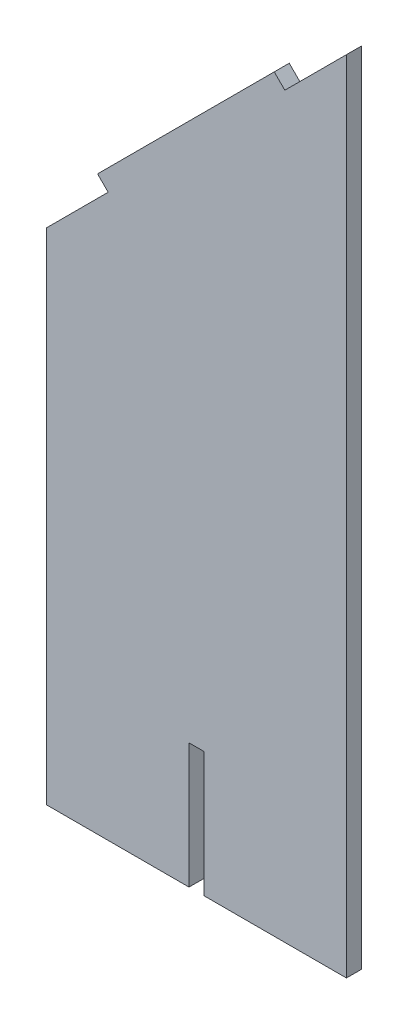
SolidWorks part; units mm, degrees
ref_plane "Plan de face" through (0, 0, 0) normal (0, 0, 1) x (1, 0, 0)
ref_plane "Plan de dessus" through (0, 0, 0) normal (0, 1, 0) x (1, 0, 0)
ref_plane "Plan de droite" through (0, 0, 0) normal (1, 0, 0) x (0, 0, -1)
sketch "Esquisse1" plane through (0, 0, 0) normal (0, 0, 1) x (1, 0, 0)
  line L1 (0, 0) -> (28.5, 0)
  line L2 (0, 0) -> (0, 100)
  line L3 (0, 100) -> (60, 100)
  line L4 (60, 0) -> (60, 100)
  line L5 (60, 100) -> (0, 100)
  line L9 (60, 160) -> (60, 100)
  line L10 (28.5, 0) -> (28.5, 25)
  line L11 (28.5, 25) -> (31.5, 25)
  line L12 (31.5, 25) -> (31.5, 0)
  line L13 (0, 100) -> (12.3213, 112.3213)
  line L14 (12.3213, 112.3213) -> (10.2, 114.4427)
  line L15 (10.2, 114.4427) -> (45.5554, 149.798)
  line L16 (31.5, 0) -> (60, 0)
  line L17 (45.5554, 149.798) -> (47.6767, 147.6767)
  line L18 (47.6767, 147.6767) -> (60, 160)
  point P8 (30, 25)
  dimension "D1" = 60
  dimension "D2" = 100
  dimension "D3" = 84.8528
  dimension "D4" = 3
  dimension "D5" = 25
  dimension "D8" = 17.425
  dimension "D9" = 50
  dimension "D10" = 3
extrude "Boss.-Extru.1" add sketch "Esquisse1" along normal blind 3
